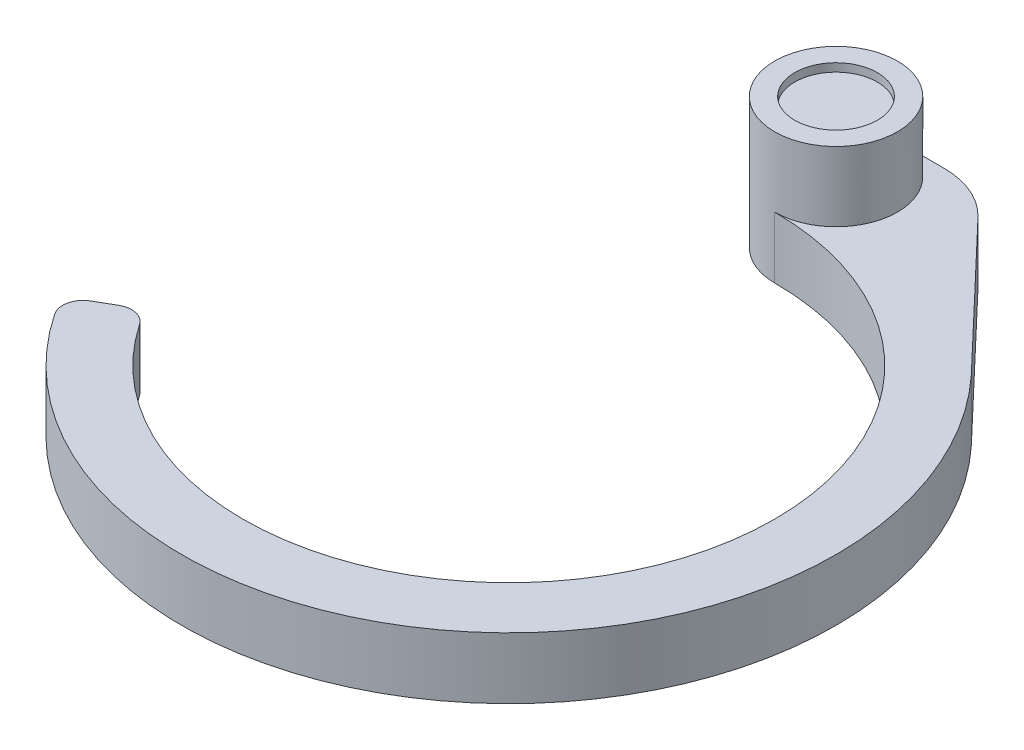
SolidWorks part; units mm, degrees
ref_plane "正面" through (0, 0, 0) normal (0, 0, 1) x (1, 0, 0)
ref_plane "平面" through (0, 0, 0) normal (0, 1, 0) x (1, 0, 0)
ref_plane "右側面" through (0, 0, 0) normal (1, 0, 0) x (0, 0, -1)
sketch "ｽｹｯﾁ2" plane through (0, 0, 0) normal (0, 1, 0) x (1, 0, 0)
  line L1 (-1.8089, 2.6033) -> (0, 0)
  line L2 (-60.4669, -34.9106) -> (-64.8074, -37.4166)
  line L4 (0, 95) -> (11.4274, 95)
  line L5 (25.9115, 88.7917) -> (58.5757, 54.4875)
  arc A0 (-66.4612, -44.5298) -> (57.2894, 55.8384) centre (0, 0) ccw
  arc A1 (-53.8264, -36.4378) -> (0, 65) centre (0, 0) ccw
  arc A2 (0, 95) -> (0, 65) centre (0, 80) ccw
  arc A3 (11.4274, 95) -> (25.9115, 88.7917) centre (11.4274, 75) cw
  arc A4 (-53.8264, -36.4378) -> (-60.4669, -34.9106) centre (-57.9669, -39.2407) ccw
  arc A5 (-66.4612, -44.5298) -> (-64.8074, -37.4166) centre (-62.3074, -41.7467) cw
  dimension "D1" = 160
  dimension "D2" = 130
  dimension "D4" = 20
  dimension "D5" = 5
  dimension "D6" = 5
extrude "ﾎﾞｽ - 押し出し4" add sketch "ｽｹｯﾁ2" along normal blind 15 contours A5 A0 L5 A3 L4 A2 A1 A4 L2
sketch "ｽｹｯﾁ4" plane through (0, 15, 0) normal (0, 1, 0) x (1, 0, 0)
  circle A0 centre (0, 80) radius 15
extrude "ﾎﾞｽ - 押し出し5" add sketch "ｽｹｯﾁ4" along normal blind 17
sketch "ｽｹｯﾁ6" plane through (0, 32, 0) normal (0, 1, 0) x (1, 0, 0)
  circle A0 centre (0, 80) radius 10.1
extrude "ｶｯﾄ - 押し出し1" cut sketch "ｽｹｯﾁ6" against normal blind 2
